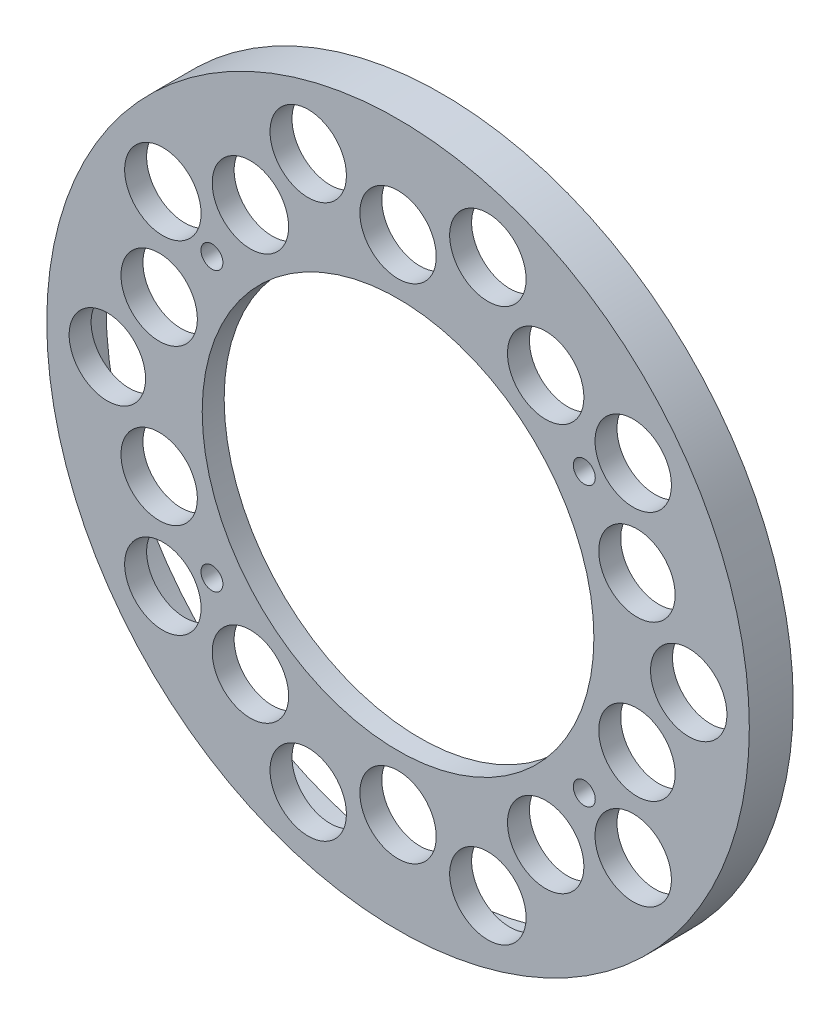
SolidWorks part; units mm, degrees
ref_plane "Front Plane" through (0, 0, 0) normal (0, 0, 1) x (1, 0, 0)
ref_plane "Top Plane" through (0, 0, 0) normal (0, 1, 0) x (1, 0, 0)
ref_plane "Right Plane" through (0, 0, 0) normal (1, 0, 0) x (0, 0, -1)
sketch "Sketch1" plane through (0, 0, 0) normal (0, 0, 1) x (1, 0, 0)
  circle A0 centre (0, 0) radius 101.6
  dimension "D1" = 203.2
extrude "Boss-Extrude1" add sketch "Sketch1" along normal blind 6.35
sketch "Sketch2" plane through (0, 0, 6.35) normal (0, 0, 1) x (1, 0, 0)
  circle A0 centre (0, 0) radius 56.642
  dimension "D1" = 113.284
extrude "Cut-Extrude1" cut sketch "Sketch2" against normal blind 146.304
sketch "Sketch3" plane through (0, 0, 6.35) normal (0, 0, 1) x (1, 0, 0)
  circle A1 centre (0, 72.644) radius 11.049
  circle A2 centre (42.6991, 58.7702) radius 11.049
  circle A3 centre (69.0885, 22.4482) radius 11.049
  circle A4 centre (69.0885, -22.4482) radius 11.049
  circle A5 centre (42.6991, -58.7702) radius 11.049
  circle A6 centre (0, -72.644) radius 11.049
  circle A7 centre (-42.6991, -58.7702) radius 11.049
  circle A8 centre (-69.0885, -22.4482) radius 11.049
  circle A9 centre (-69.0885, 22.4482) radius 11.049
  circle A10 centre (-42.6991, 58.7702) radius 11.049
  point P28 (0, 0)
  dimension "D2" = 22.098
  dimension "D3" = 10
extrude "Cut-Extrude2" cut sketch "Sketch3" against normal blind 146.304
sketch "Sketch4" plane through (0, 0, 6.35) normal (0, 0, 1) x (1, 0, 0)
  circle A2 centre (84.074, 0) radius 11.049
  circle A3 centre (68.0173, -49.4175) radius 11.049
  circle A4 centre (25.9803, -79.9591) radius 11.049
  circle A5 centre (-25.9803, -79.9591) radius 11.049
  circle A6 centre (-68.0173, -49.4175) radius 11.049
  circle A7 centre (-84.074, 0) radius 11.049
  circle A8 centre (-68.0173, 49.4175) radius 11.049
  circle A9 centre (-25.9803, 79.9591) radius 11.049
  circle A10 centre (25.9803, 79.9591) radius 11.049
  circle A11 centre (68.0173, 49.4175) radius 11.049
  point P24 (0, 0)
  dimension "D2" = 22.098
  dimension "D1" = 10
extrude "Cut-Extrude3" cut sketch "Sketch4" against normal blind 146.304
sketch "Sketch5" plane through (0, 0, 6.35) normal (0, 0, 1) x (1, 0, 0)
  circle A0 centre (53.8676, 40.259) radius 3.175
  circle A1 centre (-53.8284, 40.259) radius 3.175
  circle A4 centre (-53.8284, -40.259) radius 3.175
  circle A5 centre (53.8676, -40.259) radius 3.175
  dimension "D1" = 6.35
  dimension "D2" = 6.35
  dimension "D5" = 6.35
  dimension "D6" = 6.35
extrude "Cut-Extrude4" cut sketch "Sketch5" against normal blind 146.304
sketch "Sketch6" plane through (0, 0, 0) normal (0, 0, -1) x (-1, 0, 0)
  circle A0 centre (0, 0) radius 101.6
  circle A1 centre (0, 0) radius 97.155
  dimension "D1" = 194.31
extrude "Boss-Extrude2" add sketch "Sketch6" along normal blind 6.35
